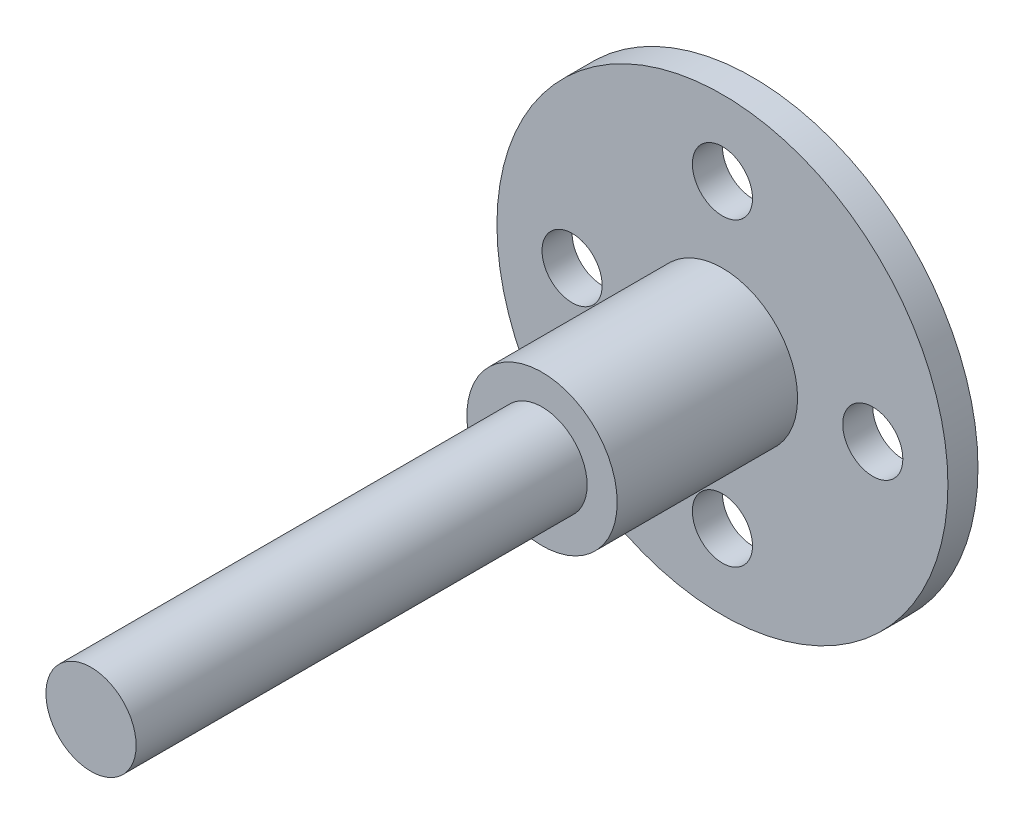
SolidWorks part; units mm, degrees
material "1060 Alloy"
ref_plane "Front Plane" through (0, 0, 0) normal (0, 0, 1) x (1, 0, 0)
ref_plane "Top Plane" through (0, 0, 0) normal (0, 1, 0) x (1, 0, 0)
ref_plane "Right Plane" through (0, 0, 0) normal (1, 0, 0) x (0, 0, -1)
sketch "Sketch1" plane through (0, 0, 0) normal (0, 0, 1) x (1, 0, 0)
  circle A0 centre (0, 0) radius 15
  dimension "D1" = 30
extrude "Boss-Extrude1" add sketch "Sketch1" along normal blind 2
sketch "Sketch2" plane through (0, 0, 2) normal (0, 0, 1) x (1, 0, 0)
  circle A0 centre (0, 0) radius 5
extrude "Boss-Extrude2" add sketch "Sketch2" along normal blind 12
sketch "Sketch3" plane through (0, 0, 2) normal (0, 0, 1) x (1, 0, 0)
  circle A0 centre (0, 10) radius 2
  circle A1 centre (10, 0) radius 2
  circle A2 centre (0, -10) radius 2
  circle A3 centre (-10, 0) radius 2
  point P12 (0, 0)
  dimension "D1" = 4
  dimension "D2" = 10
  dimension "D3" = 4
extrude "Cut-Extrude1" cut sketch "Sketch3" against normal blind 6
sketch "Sketch4" plane through (0, 0, 14) normal (0, 0, 1) x (1, 0, 0)
  circle A0 centre (0, 0) radius 3
extrude "Boss-Extrude3" add sketch "Sketch4" along normal blind 30
